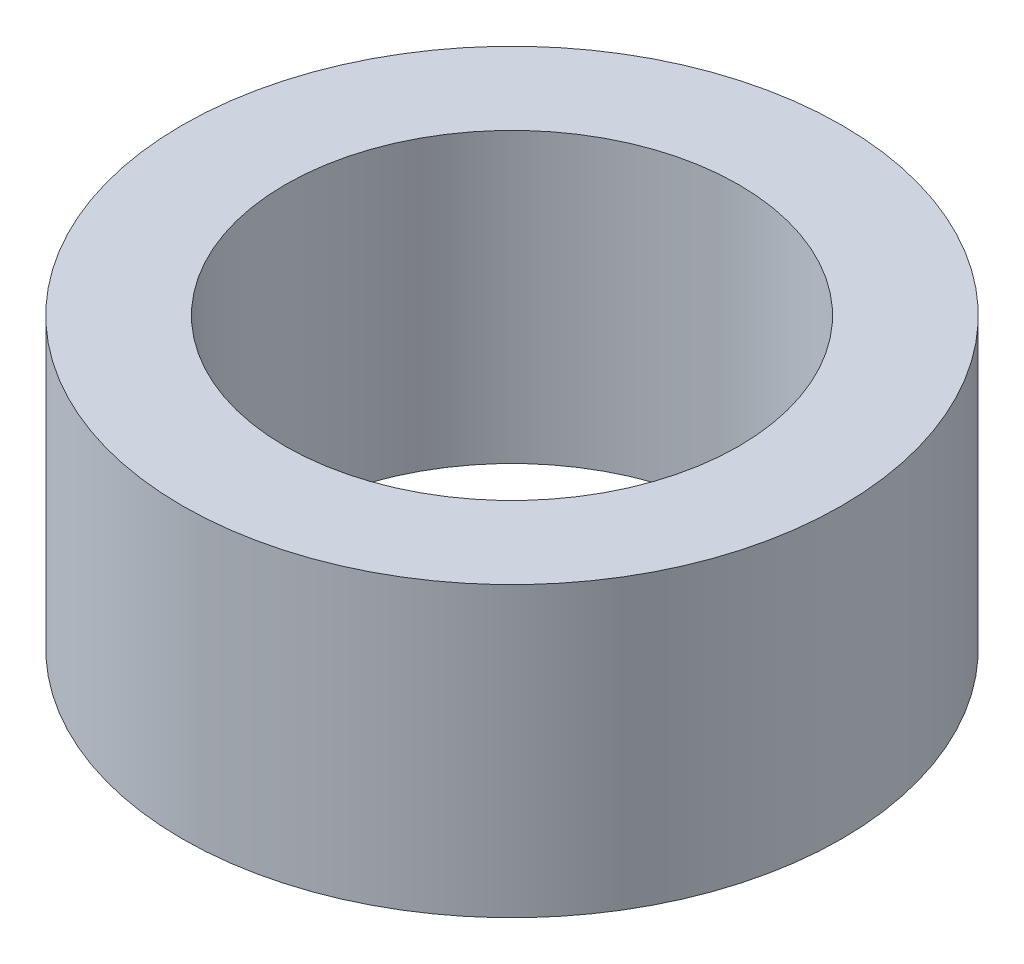
SolidWorks part; units mm, degrees
ref_plane "Front" through (0, 0, 0) normal (0, 0, 1) x (1, 0, 0)
ref_plane "Top" through (0, 0, 0) normal (0, 1, 0) x (1, 0, 0)
ref_plane "Right" through (0, 0, 0) normal (1, 0, 0) x (0, 0, -1)
sketch "Sketch1" plane through (0, 0, 0) normal (0, 1, 0) x (1, 0, 0)
  circle A0 centre (0, 0) radius 5.5
  circle A1 centre (0, 0) radius 8
  dimension "D1" = 11
  dimension "D2" = 16
extrude "Boss-Extrude1" add sketch "Sketch1" along normal blind 7
